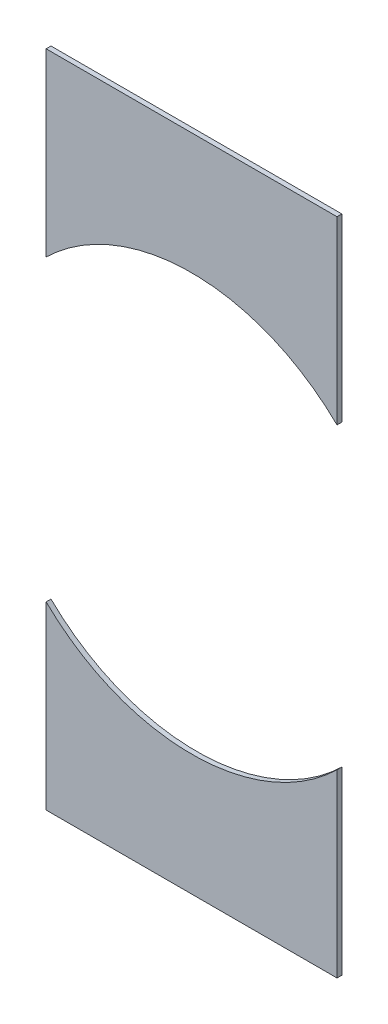
SolidWorks part; units mm, degrees
ref_plane "Alzado" through (0, 0, 0) normal (0, 0, 1) x (1, 0, 0)
ref_plane "Planta" through (0, 0, 0) normal (0, 1, 0) x (1, 0, 0)
ref_plane "Vista lateral" through (0, 0, 0) normal (1, 0, 0) x (0, 0, -1)
sketch "Croquis1" plane through (0, 0, 0) normal (0, 0, 1) x (1, 0, 0)
  line L0 (-40, 0) -> (40, 0) construction
  line L2 (0, 43) -> (0, 68) construction
  line L3 (-30, 68) -> (30, 68)
  line L4 (30, 68) -> (30, 30.8058)
  line L5 (-30, 68) -> (-30, 30.8058)
  line L6 (30, -68) -> (30, -30.8058)
  line L7 (-30, -68) -> (30, -68)
  line L8 (-30, -68) -> (-30, -30.8058)
  circle A1 centre (0, 0) radius 43
  point P1 (0, 0)
  point P5 (0, 0)
  point P6 (0, 0)
  dimension "D1" = 30
  dimension "D2" = 25
extrude "Saliente-Extruir1" add sketch "Croquis1" along normal blind 1 contours A1 L4 L3 L5 | A1 L8 L7 L6
